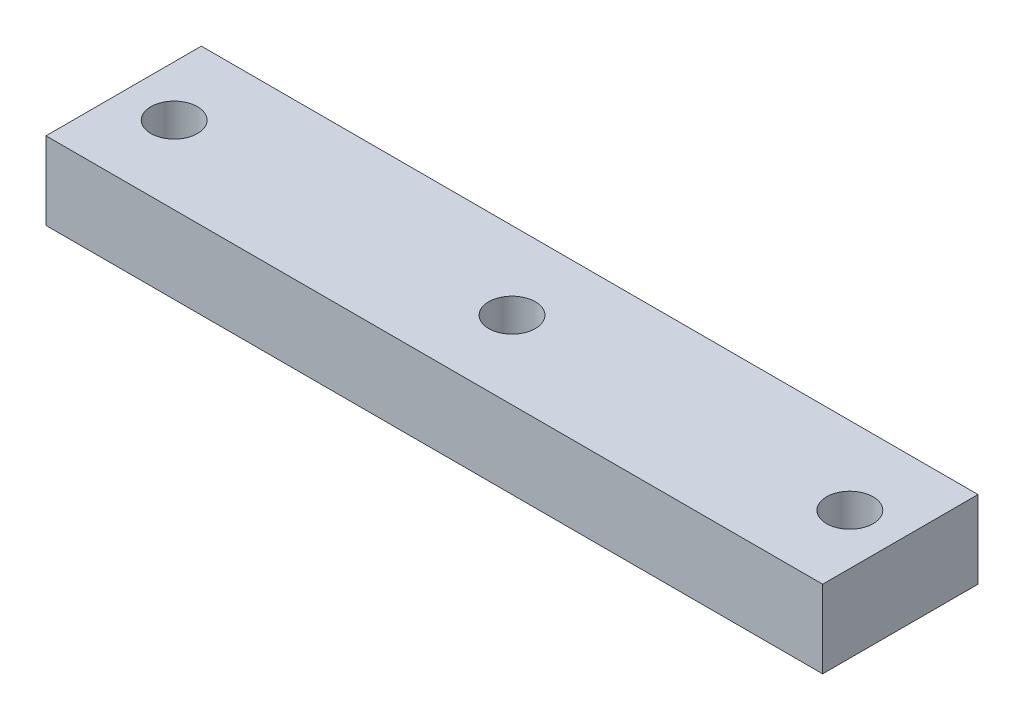
SolidWorks part; units mm, degrees
ref_plane "Front Plane" through (0, 0, 0) normal (0, 0, 1) x (1, 0, 0)
ref_plane "Top Plane" through (0, 0, 0) normal (0, 1, 0) x (1, 0, 0)
ref_plane "Right Plane" through (0, 0, 0) normal (1, 0, 0) x (0, 0, -1)
sketch "Sketch3" plane through (0, 0, 0) normal (0, 1, 0) x (1, 0, 0)
  line L1 (-1.2346, 0) -> (-51.2346, 0)
  line L2 (-1.2346, 0) -> (-1.2346, -10)
  line L3 (-1.2346, -10) -> (-51.2346, -10)
  line L4 (-51.2346, 0) -> (-51.2346, -10)
  circle A0 centre (-4.4846, -5) radius 1.5
  circle A1 centre (-26.2346, -5) radius 1.5
  circle A2 centre (-47.9846, -5) radius 1.5
  dimension "D3" = 3
  dimension "D1" = 50
  dimension "D2" = 10
  dimension "D4" = 5
  dimension "D6" = 3.25
  dimension "D5" = 3
extrude "Boss-Extrude2" add sketch "Sketch3" along normal blind 5
equation "\"D6@Sketch3\"=25-21.75"
